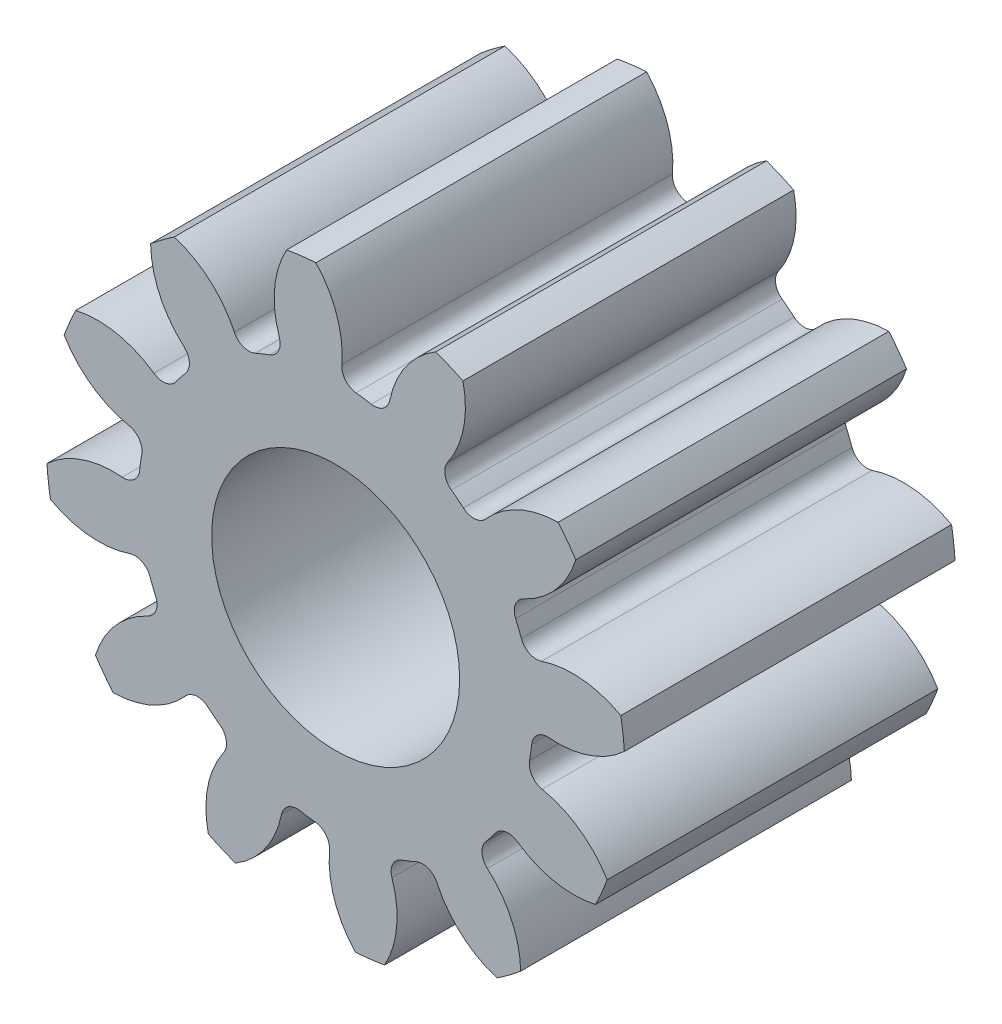
SolidWorks part; units mm, degrees
ref_plane "Front" through (0, 0, 0) normal (0, 0, 1) x (1, 0, 0)
ref_plane "Top" through (0, 0, 0) normal (0, 1, 0) x (1, 0, 0)
ref_plane "Right" through (0, 0, 0) normal (1, 0, 0) x (0, 0, -1)
sketch "Sketch3" plane through (0, 0, 0) normal (0, 0, 1) x (1, 0, 0)
  circle A0 centre (0, 0) radius 11.1125
  dimension "od" = 22.225
extrude "gearBody" add sketch "Sketch3" along normal blind 12.7
sketch "Sketch2" plane through (0, 0, 0) normal (0, 0, 1) x (1, 0, 0)
  line L0 (0, 0) -> (8.5197, 3.529) construction
  line L1 (10.7769, -4.6208) -> (0, 0) construction
  line L2 (0, 0) -> (36.3143, 0) construction
  line L3 (9.5243, -0.1145) -> (9.1712, -2.572) construction
  line L5 (9.3477, -1.3432) -> (0, 0) construction
  line L7 (0, 0) -> (9.2216, 0) construction
  arc A0 (9.2197, -0.1851) -> (8.8988, -2.4185) centre (0, 0) ccw construction
  arc A1 (11.0868, 0.7552) -> (10.4256, -3.8464) centre (0, 0) ccw construction
  arc A2 (9.5243, -0.1145) -> (9.1712, -2.572) centre (0, 0) ccw construction
  arc A3 (7.4448, -1.3669) -> (7.5284, -0.7847) centre (0, 0) ccw
  arc A4 (10.7769, -4.6208) -> (7.9277, -2.0801) centre (7.1813, -5.7851) ccw
  arc A5 (10.7769, -4.6208) -> (11.642, 1.3993) centre (0, 0) ccw
  arc A6 (11.642, 1.3993) -> (8.1926, -0.2363) centre (8.5197, 3.529) cw
  arc A7 (7.5284, -0.7847) -> (8.1926, -0.2363) centre (8.1395, -0.8484) cw
  arc A8 (7.9277, -2.0801) -> (7.4448, -1.3669) centre (8.049, -1.4778) cw
  point P6 (11.642, 1.3993)
  point P22 (10.7769, -4.6208)
  dimension "baseDia" = 18.4432
  dimension "od" = 22.225
  dimension "pd" = 19.05
  dimension "rd" = 15.1384
  dimension "rFillet" = 0.6144
  dimension "pointX" = 11.642
  dimension "pointY" = 1.3993
  dimension "CTT" = 2.4574
  dimension "flankCenterAngle" = 22.5
extrude "toothCut" cut sketch "Sketch2" along normal through all
pattern_circular "CirPattern1" count 12 over 360 about axis through (0, 0, 0) along (0, 0, 1) of "toothCut"
sketch "hub1Dia" plane through (0, 0, 0) normal (0, 0, -1) x (-1, 0, 0)
  circle A0 centre (0, 0) radius 12.7
  dimension "hub1Dia" = 25.4
sketch "hub2Dia" plane through (0, 0, 12.7) normal (0, 0, 1) x (1, 0, 0)
  circle A0 centre (0, 0) radius 12.7
  dimension "hub2dia" = 25.4
sketch "boreDia" plane through (0, 0, 0) normal (0, 0, 1) x (1, 0, 0)
  circle A0 centre (0, 0) radius 4.7625
  dimension "boreDia" = 9.525
extrude "bore" cut sketch "boreDia" against normal mid plane 25400
